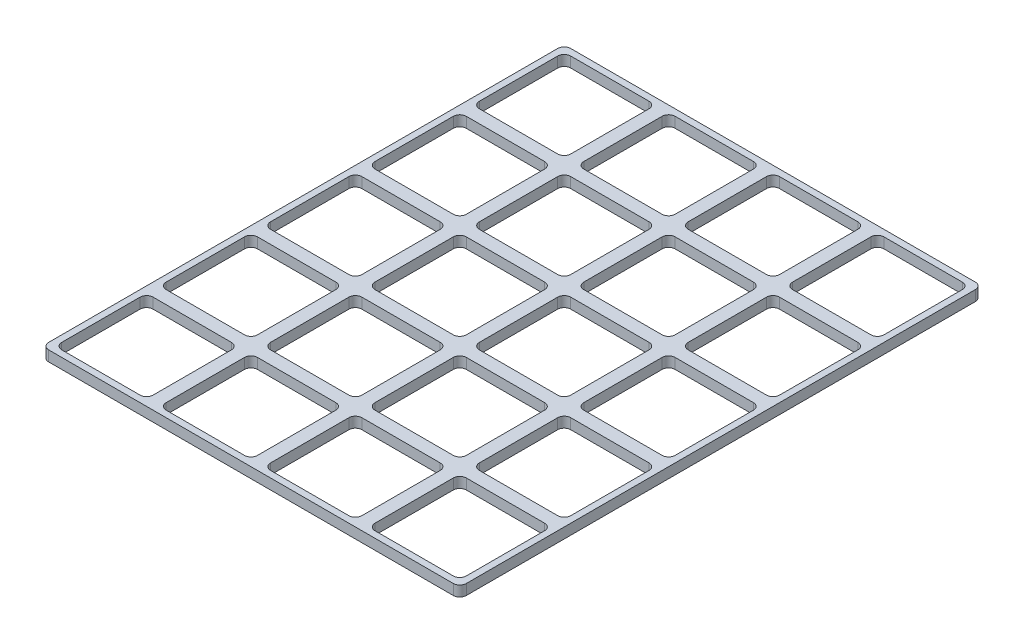
SolidWorks part; units mm, degrees
ref_plane "Front Plane" through (0, 0, 0) normal (0, 0, 1) x (1, 0, 0)
ref_plane "Top Plane" through (0, 0, 0) normal (0, 1, 0) x (1, 0, 0)
ref_plane "Right Plane" through (0, 0, 0) normal (1, 0, 0) x (0, 0, -1)
sketch "Sketch1" plane through (0, 0, 0) normal (0, 1, 0) x (1, 0, 0)
  line L1 (80, -100) -> (-80, -100)
  line L2 (80, -100) -> (80, 100)
  line L3 (80, 100) -> (-80, 100)
  line L4 (-80, -100) -> (-80, 100)
  line L5 (80, -100) -> (-80, 100) construction
  line L6 (80, 100) -> (-80, -100) construction
  point P0 (0, 0)
  dimension "D1" = 160
  dimension "D2" = 200
extrude "Boss-Extrude1" add sketch "Sketch1" along normal blind 4
sketch "Sketch3" plane through (0, 4, 0) normal (0, 1, 0) x (1, 0, 0)
  line L0 (-5, -97.5) -> (-35, -97.5)
  line L1 (-80, -100) -> (-40, -100) construction
  line L2 (-80, -100) -> (-80, -60) construction
  line L3 (-80, -60) -> (-40, -60) construction
  line L4 (-40, -100) -> (-40, -60) construction
  line L5 (-80, -100) -> (-40, -60) construction
  line L6 (-80, -60) -> (-40, -100) construction
  line L7 (-45, -97.5) -> (-75, -97.5)
  line L8 (-42.5, -95) -> (-42.5, -65)
  line L9 (-45, -62.5) -> (-75, -62.5)
  line L10 (-77.5, -95) -> (-77.5, -65)
  line L11 (-42.5, -97.5) -> (-77.5, -62.5) construction
  line L12 (-42.5, -62.5) -> (-77.5, -97.5) construction
  line L13 (-2.5, -95) -> (-2.5, -65)
  line L14 (-5, -62.5) -> (-35, -62.5)
  line L15 (-37.5, -95) -> (-37.5, -65)
  line L16 (-40, -100) -> (0, -100) construction
  line L17 (-40, -100) -> (-40, -60) construction
  line L18 (-40, -60) -> (0, -60) construction
  line L19 (0, -100) -> (0, -60) construction
  line L20 (-40, -100) -> (0, -60) construction
  line L21 (-40, -60) -> (0, -100) construction
  line L22 (-2.5, -97.5) -> (-37.5, -62.5) construction
  line L23 (-2.5, -62.5) -> (-37.5, -97.5) construction
  line L24 (35, -97.5) -> (5, -97.5)
  line L25 (37.5, -95) -> (37.5, -65)
  line L26 (35, -62.5) -> (5, -62.5)
  line L27 (2.5, -95) -> (2.5, -65)
  line L28 (0, -100) -> (40, -100) construction
  line L29 (0, -100) -> (0, -60) construction
  line L30 (0, -60) -> (40, -60) construction
  line L31 (40, -100) -> (40, -60) construction
  line L32 (0, -100) -> (40, -60) construction
  line L33 (0, -60) -> (40, -100) construction
  line L34 (37.5, -97.5) -> (2.5, -62.5) construction
  line L35 (37.5, -62.5) -> (2.5, -97.5) construction
  line L36 (75, -97.5) -> (45, -97.5)
  line L37 (77.5, -95) -> (77.5, -65)
  line L38 (75, -62.5) -> (45, -62.5)
  line L39 (42.5, -95) -> (42.5, -65)
  line L40 (40, -100) -> (80, -100) construction
  line L41 (40, -100) -> (40, -60) construction
  line L42 (40, -60) -> (80, -60) construction
  line L43 (80, -100) -> (80, -60) construction
  line L44 (40, -100) -> (80, -60) construction
  line L45 (40, -60) -> (80, -100) construction
  line L46 (77.5, -97.5) -> (42.5, -62.5) construction
  line L47 (77.5, -62.5) -> (42.5, -97.5) construction
  line L48 (-5, -57.5) -> (-35, -57.5)
  line L49 (-2.5, -55) -> (-2.5, -25)
  line L50 (-5, -22.5) -> (-35, -22.5)
  line L51 (-37.5, -55) -> (-37.5, -25)
  line L52 (-40, -60) -> (0, -60) construction
  line L53 (-40, -60) -> (-40, -20) construction
  line L54 (-40, -20) -> (0, -20) construction
  line L55 (0, -60) -> (0, -20) construction
  line L56 (-40, -60) -> (0, -20) construction
  line L57 (-40, -20) -> (0, -60) construction
  line L58 (-2.5, -57.5) -> (-37.5, -22.5) construction
  line L59 (-2.5, -22.5) -> (-37.5, -57.5) construction
  line L60 (35, -57.5) -> (5, -57.5)
  line L61 (37.5, -55) -> (37.5, -25)
  line L62 (35, -22.5) -> (5, -22.5)
  line L63 (2.5, -55) -> (2.5, -25)
  line L64 (0, -60) -> (40, -60) construction
  line L65 (0, -60) -> (0, -20) construction
  line L66 (0, -20) -> (40, -20) construction
  line L67 (40, -60) -> (40, -20) construction
  line L68 (0, -60) -> (40, -20) construction
  line L69 (0, -20) -> (40, -60) construction
  line L70 (37.5, -57.5) -> (2.5, -22.5) construction
  line L71 (37.5, -22.5) -> (2.5, -57.5) construction
  line L72 (75, -57.5) -> (45, -57.5)
  line L73 (77.5, -55) -> (77.5, -25)
  line L74 (75, -22.5) -> (45, -22.5)
  line L75 (42.5, -55) -> (42.5, -25)
  line L76 (40, -60) -> (80, -60) construction
  line L77 (40, -60) -> (40, -20) construction
  line L78 (40, -20) -> (80, -20) construction
  line L79 (80, -60) -> (80, -20) construction
  line L80 (40, -60) -> (80, -20) construction
  line L81 (40, -20) -> (80, -60) construction
  line L82 (77.5, -57.5) -> (42.5, -22.5) construction
  line L83 (77.5, -22.5) -> (42.5, -57.5) construction
  line L84 (-5, -17.5) -> (-35, -17.5)
  line L85 (-2.5, -15) -> (-2.5, 15)
  line L86 (-5, 17.5) -> (-35, 17.5)
  line L87 (-37.5, -15) -> (-37.5, 15)
  line L88 (-40, -20) -> (0, -20) construction
  line L89 (-40, -20) -> (-40, 20) construction
  line L90 (-40, 20) -> (0, 20) construction
  line L91 (0, -20) -> (0, 20) construction
  line L92 (-40, -20) -> (0, 20) construction
  line L93 (-40, 20) -> (0, -20) construction
  line L94 (-2.5, -17.5) -> (-37.5, 17.5) construction
  line L95 (-2.5, 17.5) -> (-37.5, -17.5) construction
  line L96 (35, -17.5) -> (5, -17.5)
  line L97 (37.5, -15) -> (37.5, 15)
  line L98 (35, 17.5) -> (5, 17.5)
  line L99 (2.5, -15) -> (2.5, 15)
  line L100 (0, -20) -> (40, -20) construction
  line L101 (0, -20) -> (0, 20) construction
  line L102 (0, 20) -> (40, 20) construction
  line L103 (40, -20) -> (40, 20) construction
  line L104 (0, -20) -> (40, 20) construction
  line L105 (0, 20) -> (40, -20) construction
  line L106 (37.5, -17.5) -> (2.5, 17.5) construction
  line L107 (37.5, 17.5) -> (2.5, -17.5) construction
  line L108 (75, -17.5) -> (45, -17.5)
  line L109 (77.5, -15) -> (77.5, 15)
  line L110 (75, 17.5) -> (45, 17.5)
  line L111 (42.5, -15) -> (42.5, 15)
  line L112 (40, -20) -> (80, -20) construction
  line L113 (40, -20) -> (40, 20) construction
  line L114 (40, 20) -> (80, 20) construction
  line L115 (80, -20) -> (80, 20) construction
  line L116 (40, -20) -> (80, 20) construction
  line L117 (40, 20) -> (80, -20) construction
  line L118 (77.5, -17.5) -> (42.5, 17.5) construction
  line L119 (77.5, 17.5) -> (42.5, -17.5) construction
  line L120 (-5, 22.5) -> (-35, 22.5)
  line L121 (-2.5, 25) -> (-2.5, 55)
  line L122 (-5, 57.5) -> (-35, 57.5)
  line L123 (-37.5, 25) -> (-37.5, 55)
  line L124 (-40, 20) -> (0, 20) construction
  line L125 (-40, 20) -> (-40, 60) construction
  line L126 (-40, 60) -> (0, 60) construction
  line L127 (0, 20) -> (0, 60) construction
  line L128 (-40, 20) -> (0, 60) construction
  line L129 (-40, 60) -> (0, 20) construction
  line L130 (-2.5, 22.5) -> (-37.5, 57.5) construction
  line L131 (-2.5, 57.5) -> (-37.5, 22.5) construction
  line L132 (35, 22.5) -> (5, 22.5)
  line L133 (37.5, 25) -> (37.5, 55)
  line L134 (35, 57.5) -> (5, 57.5)
  line L135 (2.5, 25) -> (2.5, 55)
  line L136 (0, 20) -> (40, 20) construction
  line L137 (0, 20) -> (0, 60) construction
  line L138 (0, 60) -> (40, 60) construction
  line L139 (40, 20) -> (40, 60) construction
  line L140 (0, 20) -> (40, 60) construction
  line L141 (0, 60) -> (40, 20) construction
  line L142 (37.5, 22.5) -> (2.5, 57.5) construction
  line L143 (37.5, 57.5) -> (2.5, 22.5) construction
  line L144 (75, 22.5) -> (45, 22.5)
  line L145 (77.5, 25) -> (77.5, 55)
  line L146 (75, 57.5) -> (45, 57.5)
  line L147 (42.5, 25) -> (42.5, 55)
  line L148 (40, 20) -> (80, 20) construction
  line L149 (40, 20) -> (40, 60) construction
  line L150 (40, 60) -> (80, 60) construction
  line L151 (80, 20) -> (80, 60) construction
  line L152 (40, 20) -> (80, 60) construction
  line L153 (40, 60) -> (80, 20) construction
  line L154 (77.5, 22.5) -> (42.5, 57.5) construction
  line L155 (77.5, 57.5) -> (42.5, 22.5) construction
  line L156 (-5, 62.5) -> (-35, 62.5)
  line L157 (-2.5, 65) -> (-2.5, 95)
  line L158 (-5, 97.5) -> (-35, 97.5)
  line L159 (-37.5, 65) -> (-37.5, 95)
  line L160 (-40, 60) -> (0, 60) construction
  line L161 (-40, 60) -> (-40, 100) construction
  line L162 (-40, 100) -> (0, 100) construction
  line L163 (0, 60) -> (0, 100) construction
  line L164 (-40, 60) -> (0, 100) construction
  line L165 (-40, 100) -> (0, 60) construction
  line L166 (-2.5, 62.5) -> (-37.5, 97.5) construction
  line L167 (-2.5, 97.5) -> (-37.5, 62.5) construction
  line L168 (35, 62.5) -> (5, 62.5)
  line L169 (37.5, 65) -> (37.5, 95)
  line L170 (35, 97.5) -> (5, 97.5)
  line L171 (2.5, 65) -> (2.5, 95)
  line L172 (0, 60) -> (40, 60) construction
  line L173 (0, 60) -> (0, 100) construction
  line L174 (0, 100) -> (40, 100) construction
  line L175 (40, 60) -> (40, 100) construction
  line L176 (0, 60) -> (40, 100) construction
  line L177 (0, 100) -> (40, 60) construction
  line L178 (37.5, 62.5) -> (2.5, 97.5) construction
  line L179 (37.5, 97.5) -> (2.5, 62.5) construction
  line L180 (75, 62.5) -> (45, 62.5)
  line L181 (77.5, 65) -> (77.5, 95)
  line L182 (75, 97.5) -> (45, 97.5)
  line L183 (42.5, 65) -> (42.5, 95)
  line L184 (40, 60) -> (80, 60) construction
  line L185 (40, 60) -> (40, 100) construction
  line L186 (40, 100) -> (80, 100) construction
  line L187 (80, 60) -> (80, 100) construction
  line L188 (40, 60) -> (80, 100) construction
  line L189 (40, 100) -> (80, 60) construction
  line L190 (77.5, 62.5) -> (42.5, 97.5) construction
  line L191 (77.5, 97.5) -> (42.5, 62.5) construction
  line L192 (-45, -57.5) -> (-75, -57.5)
  line L193 (-42.5, -55) -> (-42.5, -25)
  line L194 (-45, -22.5) -> (-75, -22.5)
  line L195 (-77.5, -55) -> (-77.5, -25)
  line L196 (-80, -60) -> (-40, -60) construction
  line L197 (-80, -60) -> (-80, -20) construction
  line L198 (-80, -20) -> (-40, -20) construction
  line L199 (-40, -60) -> (-40, -20) construction
  line L200 (-80, -60) -> (-40, -20) construction
  line L201 (-80, -20) -> (-40, -60) construction
  line L202 (-42.5, -57.5) -> (-77.5, -22.5) construction
  line L203 (-42.5, -22.5) -> (-77.5, -57.5) construction
  line L204 (-45, -17.5) -> (-75, -17.5)
  line L205 (-42.5, -15) -> (-42.5, 15)
  line L206 (-45, 17.5) -> (-75, 17.5)
  line L207 (-77.5, -15) -> (-77.5, 15)
  line L208 (-80, -20) -> (-40, -20) construction
  line L209 (-80, -20) -> (-80, 20) construction
  line L210 (-80, 20) -> (-40, 20) construction
  line L211 (-40, -20) -> (-40, 20) construction
  line L212 (-80, -20) -> (-40, 20) construction
  line L213 (-80, 20) -> (-40, -20) construction
  line L214 (-42.5, -17.5) -> (-77.5, 17.5) construction
  line L215 (-42.5, 17.5) -> (-77.5, -17.5) construction
  line L216 (-45, 22.5) -> (-75, 22.5)
  line L217 (-42.5, 25) -> (-42.5, 55)
  line L218 (-45, 57.5) -> (-75, 57.5)
  line L219 (-77.5, 25) -> (-77.5, 55)
  line L220 (-80, 20) -> (-40, 20) construction
  line L221 (-80, 20) -> (-80, 60) construction
  line L222 (-80, 60) -> (-40, 60) construction
  line L223 (-40, 20) -> (-40, 60) construction
  line L224 (-80, 20) -> (-40, 60) construction
  line L225 (-80, 60) -> (-40, 20) construction
  line L226 (-42.5, 22.5) -> (-77.5, 57.5) construction
  line L227 (-42.5, 57.5) -> (-77.5, 22.5) construction
  line L228 (-45, 62.5) -> (-75, 62.5)
  line L229 (-42.5, 65) -> (-42.5, 95)
  line L230 (-45, 97.5) -> (-75, 97.5)
  line L231 (-77.5, 65) -> (-77.5, 95)
  line L232 (-80, 60) -> (-40, 60) construction
  line L233 (-80, 60) -> (-80, 100) construction
  line L234 (-80, 100) -> (-40, 100) construction
  line L235 (-40, 60) -> (-40, 100) construction
  line L236 (-80, 60) -> (-40, 100) construction
  line L237 (-80, 100) -> (-40, 60) construction
  line L238 (-42.5, 62.5) -> (-77.5, 97.5) construction
  line L239 (-42.5, 97.5) -> (-77.5, 62.5) construction
  arc A0 (-45, -62.5) -> (-42.5, -65) centre (-45, -65) cw
  arc A1 (-45, -97.5) -> (-42.5, -95) centre (-45, -95) ccw
  arc A2 (-75, -97.5) -> (-77.5, -95) centre (-75, -95) cw
  arc A3 (-77.5, -65) -> (-75, -62.5) centre (-75, -65) cw
  arc A4 (-5, -62.5) -> (-2.5, -65) centre (-5, -65) cw
  arc A5 (-5, -97.5) -> (-2.5, -95) centre (-5, -95) ccw
  arc A6 (-35, -97.5) -> (-37.5, -95) centre (-35, -95) cw
  arc A7 (-37.5, -65) -> (-35, -62.5) centre (-35, -65) cw
  arc A8 (35, -62.5) -> (37.5, -65) centre (35, -65) cw
  arc A9 (35, -97.5) -> (37.5, -95) centre (35, -95) ccw
  arc A10 (5, -97.5) -> (2.5, -95) centre (5, -95) cw
  arc A11 (2.5, -65) -> (5, -62.5) centre (5, -65) cw
  arc A12 (75, -62.5) -> (77.5, -65) centre (75, -65) cw
  arc A13 (75, -97.5) -> (77.5, -95) centre (75, -95) ccw
  arc A14 (45, -97.5) -> (42.5, -95) centre (45, -95) cw
  arc A15 (42.5, -65) -> (45, -62.5) centre (45, -65) cw
  arc A16 (-5, -22.5) -> (-2.5, -25) centre (-5, -25) cw
  arc A17 (-5, -57.5) -> (-2.5, -55) centre (-5, -55) ccw
  arc A18 (-35, -57.5) -> (-37.5, -55) centre (-35, -55) cw
  arc A19 (-37.5, -25) -> (-35, -22.5) centre (-35, -25) cw
  arc A20 (35, -22.5) -> (37.5, -25) centre (35, -25) cw
  arc A21 (35, -57.5) -> (37.5, -55) centre (35, -55) ccw
  arc A22 (5, -57.5) -> (2.5, -55) centre (5, -55) cw
  arc A23 (2.5, -25) -> (5, -22.5) centre (5, -25) cw
  arc A24 (75, -22.5) -> (77.5, -25) centre (75, -25) cw
  arc A25 (75, -57.5) -> (77.5, -55) centre (75, -55) ccw
  arc A26 (45, -57.5) -> (42.5, -55) centre (45, -55) cw
  arc A27 (42.5, -25) -> (45, -22.5) centre (45, -25) cw
  arc A28 (-5, 17.5) -> (-2.5, 15) centre (-5, 15) cw
  arc A29 (-5, -17.5) -> (-2.5, -15) centre (-5, -15) ccw
  arc A30 (-35, -17.5) -> (-37.5, -15) centre (-35, -15) cw
  arc A31 (-37.5, 15) -> (-35, 17.5) centre (-35, 15) cw
  arc A32 (35, 17.5) -> (37.5, 15) centre (35, 15) cw
  arc A33 (35, -17.5) -> (37.5, -15) centre (35, -15) ccw
  arc A34 (5, -17.5) -> (2.5, -15) centre (5, -15) cw
  arc A35 (2.5, 15) -> (5, 17.5) centre (5, 15) cw
  arc A36 (75, 17.5) -> (77.5, 15) centre (75, 15) cw
  arc A37 (75, -17.5) -> (77.5, -15) centre (75, -15) ccw
  arc A38 (45, -17.5) -> (42.5, -15) centre (45, -15) cw
  arc A39 (42.5, 15) -> (45, 17.5) centre (45, 15) cw
  arc A40 (-5, 57.5) -> (-2.5, 55) centre (-5, 55) cw
  arc A41 (-5, 22.5) -> (-2.5, 25) centre (-5, 25) ccw
  arc A42 (-35, 22.5) -> (-37.5, 25) centre (-35, 25) cw
  arc A43 (-37.5, 55) -> (-35, 57.5) centre (-35, 55) cw
  arc A44 (35, 57.5) -> (37.5, 55) centre (35, 55) cw
  arc A45 (35, 22.5) -> (37.5, 25) centre (35, 25) ccw
  arc A46 (5, 22.5) -> (2.5, 25) centre (5, 25) cw
  arc A47 (2.5, 55) -> (5, 57.5) centre (5, 55) cw
  arc A48 (75, 57.5) -> (77.5, 55) centre (75, 55) cw
  arc A49 (75, 22.5) -> (77.5, 25) centre (75, 25) ccw
  arc A50 (45, 22.5) -> (42.5, 25) centre (45, 25) cw
  arc A51 (42.5, 55) -> (45, 57.5) centre (45, 55) cw
  arc A52 (-5, 97.5) -> (-2.5, 95) centre (-5, 95) cw
  arc A53 (-5, 62.5) -> (-2.5, 65) centre (-5, 65) ccw
  arc A54 (-35, 62.5) -> (-37.5, 65) centre (-35, 65) cw
  arc A55 (-37.5, 95) -> (-35, 97.5) centre (-35, 95) cw
  arc A56 (35, 97.5) -> (37.5, 95) centre (35, 95) cw
  arc A57 (35, 62.5) -> (37.5, 65) centre (35, 65) ccw
  arc A58 (5, 62.5) -> (2.5, 65) centre (5, 65) cw
  arc A59 (2.5, 95) -> (5, 97.5) centre (5, 95) cw
  arc A60 (75, 97.5) -> (77.5, 95) centre (75, 95) cw
  arc A61 (75, 62.5) -> (77.5, 65) centre (75, 65) ccw
  arc A62 (45, 62.5) -> (42.5, 65) centre (45, 65) cw
  arc A63 (42.5, 95) -> (45, 97.5) centre (45, 95) cw
  arc A64 (-45, -22.5) -> (-42.5, -25) centre (-45, -25) cw
  arc A65 (-45, -57.5) -> (-42.5, -55) centre (-45, -55) ccw
  arc A66 (-75, -57.5) -> (-77.5, -55) centre (-75, -55) cw
  arc A67 (-77.5, -25) -> (-75, -22.5) centre (-75, -25) cw
  arc A68 (-45, 17.5) -> (-42.5, 15) centre (-45, 15) cw
  arc A69 (-45, -17.5) -> (-42.5, -15) centre (-45, -15) ccw
  arc A70 (-75, -17.5) -> (-77.5, -15) centre (-75, -15) cw
  arc A71 (-77.5, 15) -> (-75, 17.5) centre (-75, 15) cw
  arc A72 (-45, 57.5) -> (-42.5, 55) centre (-45, 55) cw
  arc A73 (-45, 22.5) -> (-42.5, 25) centre (-45, 25) ccw
  arc A74 (-75, 22.5) -> (-77.5, 25) centre (-75, 25) cw
  arc A75 (-77.5, 55) -> (-75, 57.5) centre (-75, 55) cw
  arc A76 (-45, 97.5) -> (-42.5, 95) centre (-45, 95) cw
  arc A77 (-45, 62.5) -> (-42.5, 65) centre (-45, 65) ccw
  arc A78 (-75, 62.5) -> (-77.5, 65) centre (-75, 65) cw
  arc A79 (-77.5, 95) -> (-75, 97.5) centre (-75, 95) cw
  point P4 (-60, -80)
  point P6 (-60, -80)
  point P30 (-20, -80)
  point P31 (-20, -80)
  point P52 (20, -80)
  point P53 (20, -80)
  point P74 (60, -80)
  point P75 (60, -80)
  point P96 (-20, -40)
  point P97 (-20, -40)
  point P118 (20, -40)
  point P119 (20, -40)
  point P140 (60, -40)
  point P141 (60, -40)
  point P162 (-20, 0)
  point P163 (-20, 0)
  point P184 (20, 0)
  point P185 (20, 0)
  point P206 (60, 0)
  point P207 (60, 0)
  point P228 (-20, 40)
  point P229 (-20, 40)
  point P250 (20, 40)
  point P251 (20, 40)
  point P272 (60, 40)
  point P273 (60, 40)
  point P294 (-20, 80)
  point P295 (-20, 80)
  point P316 (20, 80)
  point P317 (20, 80)
  point P338 (60, 80)
  point P339 (60, 80)
  point P360 (-60, -40)
  point P361 (-60, -40)
  point P382 (-60, 0)
  point P383 (-60, 0)
  point P404 (-60, 40)
  point P405 (-60, 40)
  point P426 (-60, 80)
  point P427 (-60, 80)
  dimension "D5" = 2.5
  dimension "D1" = 40
  dimension "D2" = 40
  dimension "D3" = 35
  dimension "D4" = 35
  dimension "D6" = 4
  dimension "D7" = 5
extrude "Cut-Extrude1" cut sketch "Sketch3" against normal through all
fillet "Fillet1" radius 2.5 4 edges at (-80, 2, -100) (80, 2, -100) (80, 2, 100) (-80, 2, 100)
